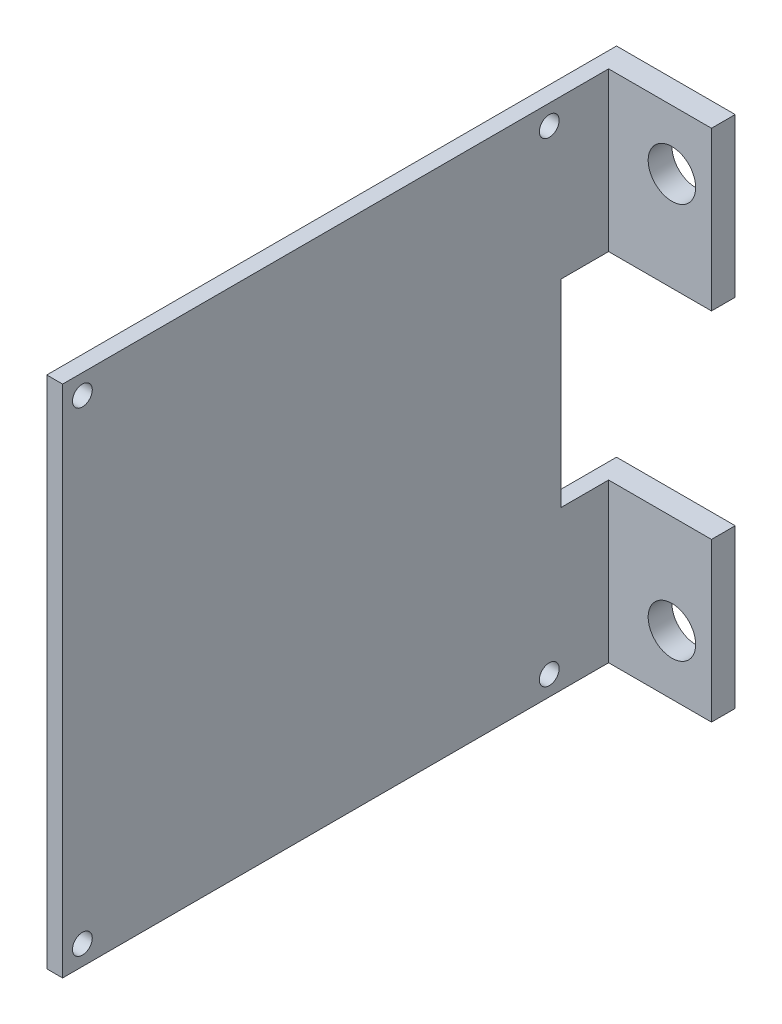
SolidWorks part; units mm, degrees
ref_plane "前基準面" through (0, 0, 0) normal (0, 0, 1) x (1, 0, 0)
ref_plane "上基準面" through (0, 0, 0) normal (0, 1, 0) x (1, 0, 0)
ref_plane "右基準面" through (0, 0, 0) normal (1, 0, 0) x (0, 0, -1)
sketch "草圖1" plane through (0, 0, 0) normal (0, 0, 1) x (1, 0, 0)
  line L1 (0, 0) -> (15, 0)
  line L2 (0, 0) -> (0, 65)
  line L3 (0, 65) -> (15, 65)
  line L4 (15, 0) -> (15, 65)
  circle A0 centre (10, 57.5) radius 3
  circle A1 centre (10, 7.5) radius 3
  dimension "D3" = 6
  dimension "D4" = 6
  dimension "D1" = 65
  dimension "D2" = 15
  dimension "D5" = 7.5
  dimension "D6" = 7.5
  dimension "D7" = 5
  dimension "D8" = 5
extrude "填料-伸長1" add sketch "草圖1" along normal blind 3 contours L4 L3 L2 L1
sketch "草圖2" plane through (0, 0, 3) normal (0, 0, 1) x (1, 0, 0)
  line L0 (0, 0) -> (15, 0) construction
  line L1 (0, 65) -> (15, 65) construction
  line L2 (15, 0) -> (15, 65) construction
  line L3 (0, 0) -> (0, 65) construction
  line L4 (0, 45) -> (15, 45)
  line L5 (0, 45) -> (0, 20)
  line L6 (0, 20) -> (15, 20)
  line L7 (15, 45) -> (15, 20)
  line L8 (15, 32.5) -> (0, 32.5) construction
  circle A0 centre (10, 57.5) radius 3
  circle A1 centre (10, 7.5) radius 3
  dimension "D1" = 6
  dimension "D2" = 6
  dimension "D3" = 7.5
  dimension "D4" = 7.5
  dimension "D5" = 5
  dimension "D6" = 5
  dimension "D7" = 25
extrude "除料-伸長1" cut sketch "草圖2" against normal blind 3
sketch "草圖4" plane through (0, 0, 3) normal (0, 0, 1) x (1, 0, 0)
  line L0 (0, 0) -> (15, 0) construction
  line L1 (0, 65) -> (2, 65)
  line L2 (0, 65) -> (0, 0)
  line L3 (0, 0) -> (2, 0)
  line L4 (2, 65) -> (2, 0)
  dimension "D1" = 2
extrude "填料-伸長2" add sketch "草圖4" along normal blind 69
sketch "草圖5" plane through (2, 0, 0) normal (1, 0, 0) x (0, 0, -1)
  line L1 (-3, 45) -> (-9, 45)
  line L2 (-3, 45) -> (-3, 20)
  line L3 (-3, 20) -> (-9, 20)
  line L4 (-9, 45) -> (-9, 20)
  dimension "D1" = 6
  dimension "D2" = 25
extrude "除料-伸長2" cut sketch "草圖5" against normal blind 69
sketch "草圖6" plane through (2, 0, 0) normal (1, 0, 0) x (0, 0, -1)
  line L0 (-69.5, 62.5) -> (-10.5, 62.5) construction
  line L1 (-10.5, 62.5) -> (-10.5, 46.6001) construction
  line L2 (-10.5, 46.6001) -> (-10.5, 2.5) construction
  line L3 (-10.5, 2.5) -> (-69.5, 2.5) construction
  line L4 (-69.5, 2.5) -> (-69.5, 62.5) construction
  line L5 (-72, 0) -> (-72, 65) construction
  circle A0 centre (-69.5, 62.5) radius 1.25
  circle A1 centre (-10.5, 62.5) radius 1.25
  circle A2 centre (-69.5, 2.5) radius 1.25
  circle A3 centre (-10.5, 2.5) radius 1.25
  point P12 (-72, 6.0045)
  dimension "D3" = 2.5
  dimension "D1" = 60
  dimension "D2" = 59
  dimension "D4" = 2.5
  dimension "D5" = 2.5
extrude "除料-伸長3" cut sketch "草圖6" against normal blind 69
